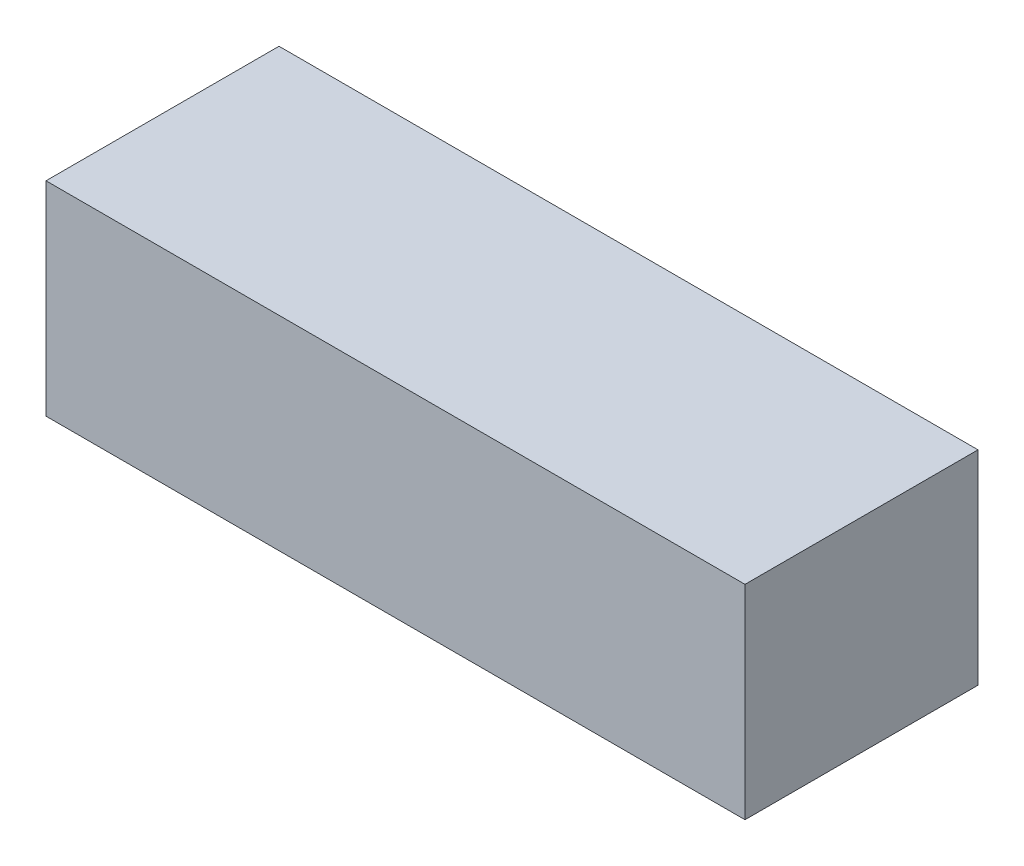
SolidWorks part; units mm, degrees
ref_plane "Front Plane" through (0, 0, 0) normal (0, 0, 1) x (1, 0, 0)
ref_plane "Top Plane" through (0, 0, 0) normal (0, 1, 0) x (1, 0, 0)
ref_plane "Right Plane" through (0, 0, 0) normal (1, 0, 0) x (0, 0, -1)
sketch "Sketch1" plane through (0, 0, 0) normal (0, 1, 0) x (1, 0, 0)
  line L1 (0, 0) -> (609.6, 0)
  line L2 (0, 0) -> (0, 203.2)
  line L3 (0, 203.2) -> (609.6, 203.2)
  line L4 (609.6, 0) -> (609.6, 203.2)
  dimension "D1" = 609.6
  dimension "D2" = 203.2
extrude "Boss-Extrude1" add sketch "Sketch1" along normal blind 177.8
